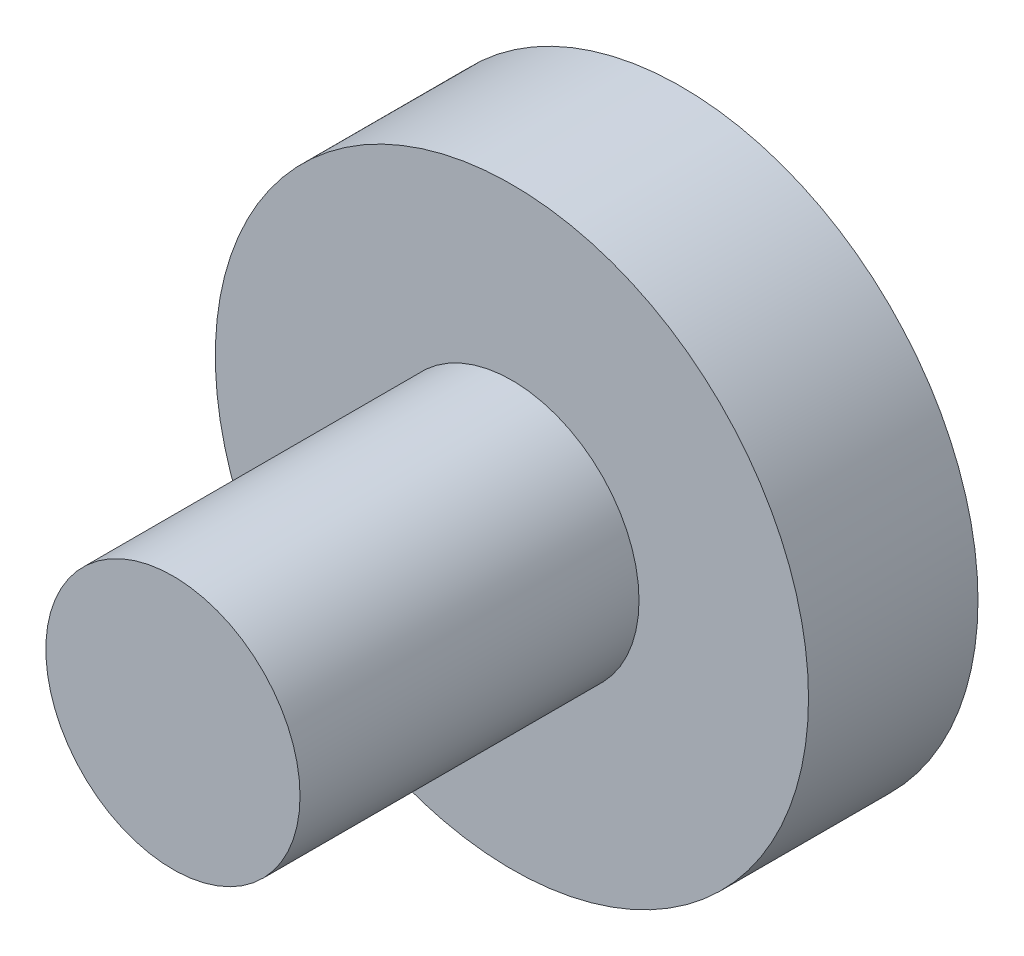
SolidWorks part; units mm, degrees
ref_plane "Płaszczyzna przednia" through (0, 0, 0) normal (0, 0, 1) x (1, 0, 0)
ref_plane "Płaszczyzna górna" through (0, 0, 0) normal (0, 1, 0) x (1, 0, 0)
ref_plane "Płaszczyzna prawa" through (0, 0, 0) normal (1, 0, 0) x (0, 0, -1)
sketch "Szkic1" plane through (0, 0, 0) normal (0, 0, 1) x (1, 0, 0)
  circle A0 centre (0, 0) radius 3.5
  dimension "D1" = 7
extrude "Dodanie-wyciągnięcie1" add sketch "Szkic1" along normal blind 2
sketch "Szkic2" plane through (0, 0, 2) normal (0, 0, 1) x (1, 0, 0)
  circle A0 centre (0, 0) radius 1.5
  dimension "D1" = 3
extrude "Dodanie-wyciągnięcie2" add sketch "Szkic2" along normal blind 4
